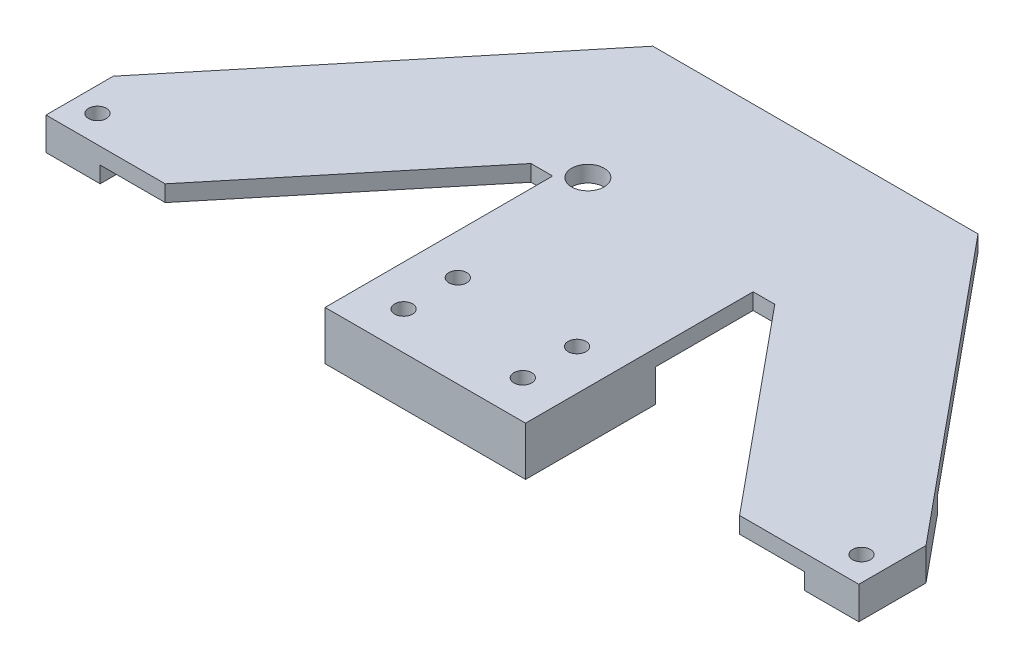
SolidWorks part; units mm, degrees
ref_plane "Front Plane" through (0, 0, 0) normal (0, 0, 1) x (1, 0, 0)
ref_plane "Top Plane" through (0, 0, 0) normal (0, 1, 0) x (1, 0, 0)
ref_plane "Right Plane" through (0, 0, 0) normal (1, 0, 0) x (0, 0, -1)
sketch "Sketch1" plane through (0, 0, 0) normal (0, 1, 0) x (1, 0, 0)
  line L0 (0, 0) -> (0, 34.9252) construction
  line L1 (-22.5, 0) -> (-18.5, 0)
  line L2 (-22.5, 0) -> (-53, -37)
  line L3 (-53, -37) -> (-75, -37)
  line L4 (-75, -24.5902) -> (-30, 30)
  line L5 (-30, 30) -> (30, 30)
  line L6 (30, 30) -> (75, -24.5902)
  line L7 (75, -37) -> (53, -37)
  line L8 (53, -37) -> (22.5, 0)
  line L10 (-18.5, 0) -> (-18.5, -42)
  line L11 (-18.5, -42) -> (18.5, -42)
  line L12 (18.5, -42) -> (18.5, 0)
  line L13 (18.5, 0) -> (22.5, 0)
  line L14 (-18.5, 0) -> (18.5, 0) construction
  line L15 (-22.5, 0) -> (22.5, 0) construction
  line L16 (-75, -24.5902) -> (-75, -37)
  line L17 (75, -24.5902) -> (75, -37)
  line L18 (-70.5, -32) -> (70.5, -32) construction
  circle A0 centre (70.5, -32) radius 1.65
  circle A1 centre (-70.5, -32) radius 1.65
  point P6 (0, 0)
  point P8 (0, 0)
  point P15 (0, 30)
  point P16 (0, 0)
  point P20 (0, 0)
  point P22 (0, -32)
  point P28 (76.5445, -37)
  dimension "D8" = 3.3
  dimension "D1" = 45
  dimension "D2" = 37
  dimension "D3" = 30
  dimension "D4" = 60
  dimension "D5" = 106
  dimension "D6" = 37
  dimension "D7" = 42
  dimension "D9" = 141
  dimension "D10" = 5
  dimension "1" = 150
extrude "Boss-Extrude1" add sketch "Sketch1" along normal blind 3
sketch "Sketch3" plane through (0, 0, 0) normal (0, 1, 0) x (1, 0, 0)
  line L0 (-18.5, -18) -> (-18.5, -42)
  line L2 (-18.5, -42) -> (18.5, -42)
  line L3 (18.5, -42) -> (18.5, -18)
  line L5 (18.5, -18) -> (-18.5, -18)
  line L6 (18.5, -42) -> (18.5, 0) construction
  dimension "D1" = 18
extrude "Boss-Extrude3" add sketch "Sketch3" against normal blind 6
sketch "Sketch4" plane through (0, 0, 0) normal (0, 1, 0) x (1, 0, 0)
  line L0 (0, -42) -> (0, -35) construction
  line L1 (-18.5, -42) -> (18.5, -42) construction
  line L2 (-11, -35) -> (11, -35) construction
  circle A0 centre (-11, -35) radius 1.65
  circle A1 centre (11, -35) radius 1.65
  circle A2 centre (-11, -25) radius 1.65
  circle A3 centre (11, -25) radius 1.65
  point P8 (0, -35)
  dimension "D1" = 3.3
  dimension "D2" = 22
  dimension "D3" = 7
  dimension "D5" = 10
  dimension "D4" = 2
extrude "Cut-Extrude1" cut sketch "Sketch4" along normal blind 10 and the other way blind 21
sketch "Sketch5" plane through (0, 0, 0) normal (0, 1, 0) x (1, 0, 0)
  arc A0 (-15, 0) -> (-15, 6) centre (-15, 3) ccw
  arc A1 (-15, 6) -> (-15, 0) centre (-15, 3) ccw
  point P1 (-15, 3)
  dimension "D2" = 3
  dimension "D1" = 15
  dimension "D3" = 3
extrude "Cut-Extrude2" cut sketch "Sketch5" along normal blind 10
sketch "Sketch6" plane through (0, 3, 0) normal (0, 1, 0) x (1, 0, 0)
  circle A0 centre (-11, -25) radius 3
  circle A1 centre (11, -25) radius 3
  circle A2 centre (11, -35) radius 3
  circle A3 centre (-11, -35) radius 3
  dimension "D1" = 6
extrude "Cut-Extrude3" [suppressed] cut sketch "Sketch6" against normal offset from surface (1 mm away) 10
sketch "Sketch7" plane through (0, 0, 0) normal (0, 1, 0) x (1, 0, 0)
  line L0 (65, -12.459) -> (65, -37)
  line L1 (30, 30) -> (75, -24.5902) construction
  line L2 (75, -37) -> (53, -37) construction
  line L3 (65, -37) -> (75, -37)
  line L4 (75, -37) -> (75, -24.5902)
  line L5 (75, -24.5902) -> (65, -12.459)
  line L6 (0, -42) -> (0, 42.5335) construction
  line L7 (-18.5, -42) -> (18.5, -42) construction
  line L8 (-75, -24.5902) -> (-65, -12.459)
  line L9 (-75, -37) -> (-75, -24.5902)
  line L10 (-65, -37) -> (-75, -37)
  line L11 (-65, -12.459) -> (-65, -37)
  circle A0 centre (70.5, -32) radius 1.65
  circle A1 centre (-70.5, -32) radius 1.65
  dimension "D1" = 10
extrude "Boss-Extrude4" add sketch "Sketch7" against normal blind 3
